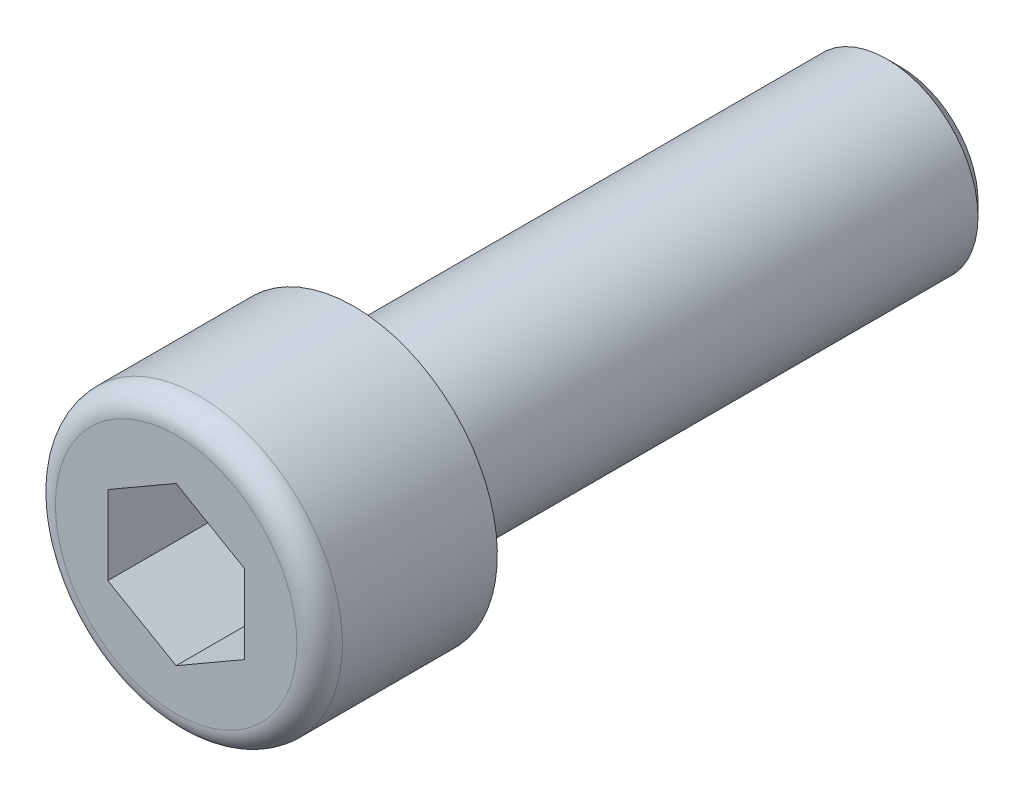
SolidWorks part; units mm, degrees
ref_plane "前视基准面" through (0, 0, 0) normal (0, 0, 1) x (1, 0, 0)
ref_plane "上视基准面" through (0, 0, 0) normal (0, 1, 0) x (1, 0, 0)
ref_plane "右视基准面" through (0, 0, 0) normal (1, 0, 0) x (0, 0, -1)
sketch "草图1" plane through (0, 0, 0) normal (1, 0, 0) x (0, 0, -1)
  line L0 (-7.95, 0) -> (-7.95, 3.15)
  line L1 (-7.95, 3.15) -> (-4.05, 3.15)
  line L2 (-4.05, 3.15) -> (-4.05, 2)
  line L3 (-4.05, 2) -> (7.95, 2)
  line L4 (7.95, 2) -> (7.95, 0)
  line L5 (7.95, 0) -> (-7.95, 0)
  point P2 (0, 0)
  dimension "D1" = 12
  dimension "D2" = 3.9
  dimension "D3" = 3.15
  dimension "D4" = 2
revolve "旋转1" add sketch "草图1" angle 360 about L5
sketch "草图2" plane through (0, 0, 7.95) normal (0, 0, 1) x (1, 0, 0)
  line L1 (0, 1.7321) -> (-1.5, 0.866)
  line L2 (-1.5, 0.866) -> (-1.5, -0.866)
  line L3 (-1.5, -0.866) -> (0, -1.7321)
  line L4 (0, -1.7321) -> (1.5, -0.866)
  line L5 (1.5, -0.866) -> (1.5, 0.866)
  line L6 (1.5, 0.866) -> (0, 1.7321)
  circle A0 centre (0, 0) radius 1.5 construction
  dimension "D1" = 3
extrude "切除-拉伸1" cut sketch "草图2" against normal blind 2.5
fillet "圆角1" radius 0.5 1 edges at (0, 3.15, 7.95)
chamfer "倒角1" distance 0.3 angle 45 1 edges at (0, 2, -7.95)
